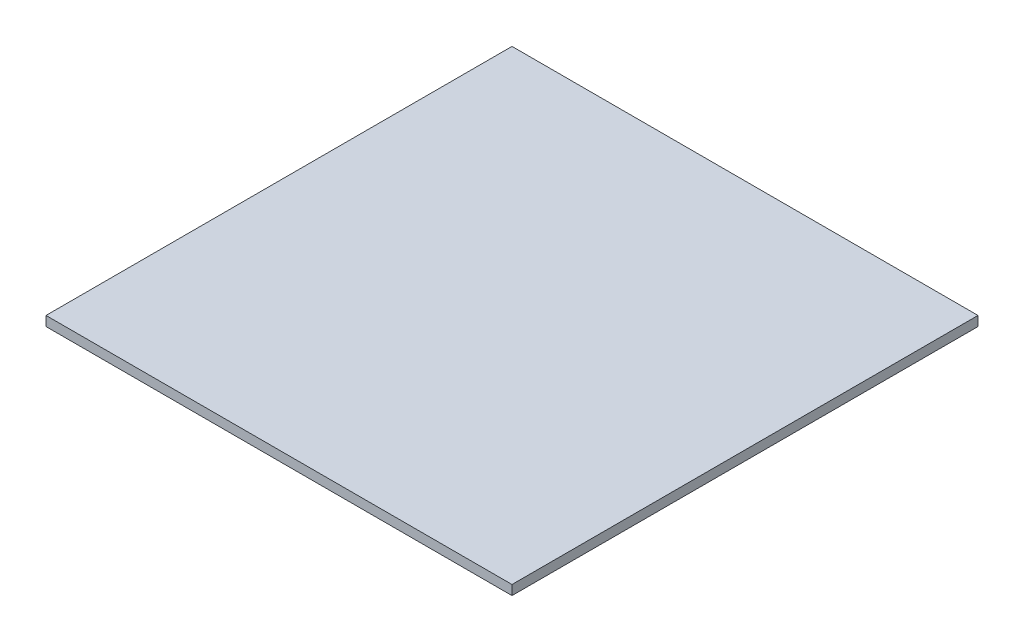
SolidWorks part; units mm, degrees
ref_plane "Front Plane" through (0, 0, 0) normal (0, 0, 1) x (1, 0, 0)
ref_plane "Top Plane" through (0, 0, 0) normal (0, 1, 0) x (1, 0, 0)
ref_plane "Right Plane" through (0, 0, 0) normal (1, 0, 0) x (0, 0, -1)
sketch "Croquis_panel" plane through (0, 0, 0) normal (0, 1, 0) x (1, 0, 0)
  line L1 (-72.5, -72.5) -> (72.5, -72.5)
  line L2 (-72.5, -72.5) -> (-72.5, 72.5)
  line L3 (-72.5, 72.5) -> (72.5, 72.5)
  line L4 (72.5, -72.5) -> (72.5, 72.5)
  line L5 (-72.5, -72.5) -> (72.5, 72.5) construction
  line L6 (-72.5, 72.5) -> (72.5, -72.5) construction
  point P0 (0, 0)
  dimension "D1" = 145
  dimension "D2" = 145
extrude "Panel" add sketch "Croquis_panel" along normal blind 3
